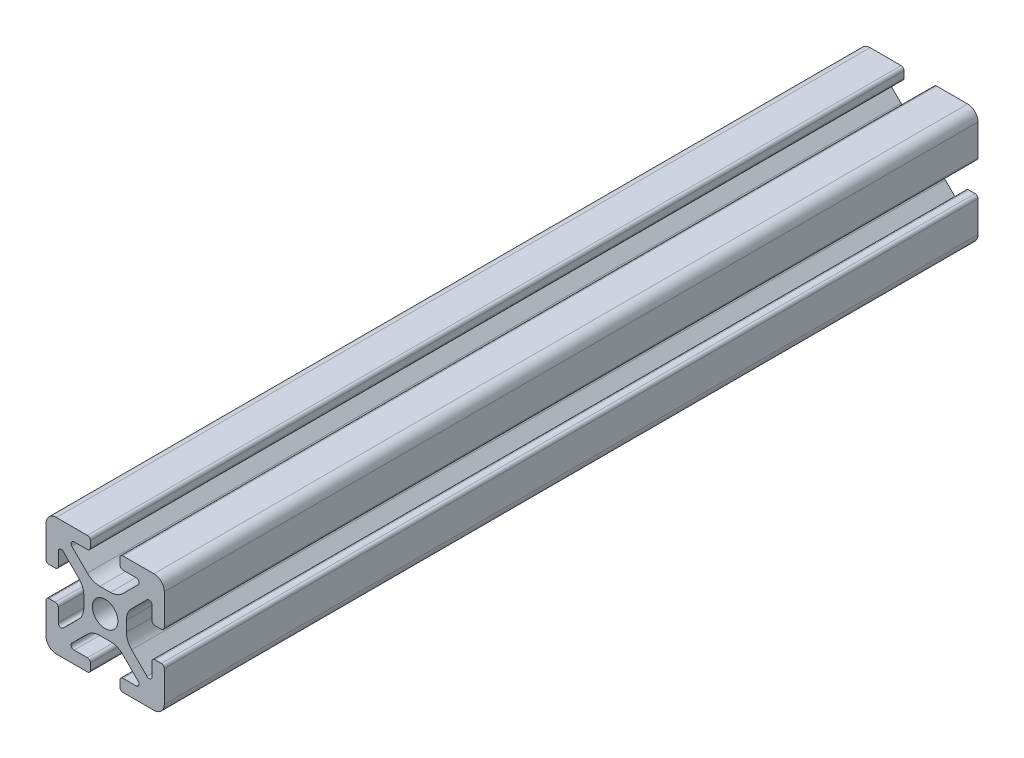
SolidWorks part; units mm, degrees
material "1060 Alloy"
ref_plane "Front Plane" through (0, 0, 0) normal (0, 0, 1) x (1, 0, 0)
ref_plane "Top Plane" through (0, 0, 0) normal (0, 1, 0) x (1, 0, 0)
ref_plane "Right Plane" through (0, 0, 0) normal (1, 0, 0) x (0, 0, -1)
sketch "Sketch2" plane through (0, 0, 0) normal (0, 0, 1) x (1, 0, 0)
  line L0 (0, 10) -> (0, -10) construction
  line L1 (-10, 0) -> (10, 0) construction
  line L2 (2.5, -10) -> (10, -10)
  line L3 (10, -10) -> (10, -2.5)
  line L4 (2.5, -10) -> (2.5, -7.9246)
  line L5 (2.5, -7.9246) -> (6.4571, -7.9246)
  line L6 (6.4571, -7.9246) -> (2.1325, -3.6)
  line L7 (0, 0) -> (10, -10) construction
  line L8 (10, -2.5) -> (7.9246, -2.5)
  line L9 (7.9246, -2.5) -> (7.9246, -6.4571)
  line L10 (7.9246, -6.4571) -> (3.6, -2.1325)
  line L11 (5.7623, -4.2948) -> (4.2948, -5.7623) construction
  circle A0 centre (0, 0) radius 2.15
  arc A1 (5.25, -7.9246) -> (5.6036, -7.0711) centre (5.25, -7.4246) ccw construction
  point P8 (0, -3.6)
  point P16 (5.0286, -5.0286)
  dimension "Center Hole Diameter" = 4.3
  dimension "D3" = 0.5
  dimension "Rail Height" = 20
  dimension "Rail Width" = 20
  dimension "T-Slot Width" = 5
  dimension "Slot Depth" = 6.4
  dimension "Slot Inner Width" = 11.5
sketch "Sketch3" plane through (0, 0, 0) normal (1, 0, 0) x (0, 0, -1)
  line L0 (-70, -10) -> (70, -10) construction
  line L1 (-44.6, 0) -> (44.6, 0) construction
  line L2 (0, 10) -> (0, -10) construction
  line L3 (0, 10) -> (0, -10) construction
  point P6 (-44.6, 0)
  point P8 (44.6, 0)
  dimension "Length" = 140
  dimension "D1" = 25.4
sketch "Sketch4" plane through (0, 0, 0) normal (0, 0, 1) x (1, 0, 0)
  line L0 (3, -10) -> (8.25, -10)
  line L1 (2.5, -10) -> (10, -10) construction
  line L2 (2.5, -10) -> (2.5, -7.9246) construction
  line L3 (2.5, -7.9246) -> (6.4571, -7.9246) construction
  line L4 (2.5, -8.4246) -> (2.5, -9.5)
  line L5 (3, -7.9246) -> (5.25, -7.9246)
  line L6 (0, -3.6) -> (0.8898, -3.6)
  line L7 (6.4571, -7.9246) -> (2.1325, -3.6) construction
  line L8 (3.0112, -4.4787) -> (5.6036, -7.0711)
  line L9 (10, -10) -> (10, -2.5) construction
  line L10 (7.9246, -6.4571) -> (3.6, -2.1325) construction
  line L11 (7.9246, -2.5) -> (7.9246, -6.4571) construction
  line L12 (7.9246, -5.25) -> (7.9246, -3)
  line L13 (10, -2.5) -> (7.9246, -2.5) construction
  line L14 (8.4246, -2.5) -> (9.5, -2.5)
  line L15 (10, -3) -> (10, -8.25)
  line L16 (7.0711, -5.6036) -> (4.4787, -3.0112)
  line L17 (3.6, 0) -> (3.6, -0.8898)
  line L18 (-10, 0) -> (10, 0) construction
  line L19 (0, -3.6) -> (0, -2.15)
  line L20 (0, 10) -> (0, -10) construction
  line L21 (3.6, 0) -> (2.15, 0)
  arc A0 (2.5, -9.5) -> (3, -10) centre (3, -9.5) ccw
  arc A1 (5.25, -7.9246) -> (5.6036, -7.0711) centre (5.25, -7.4246) ccw construction
  arc A2 (2.5, -8.4246) -> (3, -7.9246) centre (3, -8.4246) cw
  arc A3 (5.25, -7.9246) -> (5.6036, -7.0711) centre (5.25, -7.4246) ccw
  arc A4 (0.8898, -3.6) -> (3.0112, -4.4787) centre (0.8898, -6.6) cw
  arc A5 (8.25, -10) -> (10, -8.25) centre (8.25, -8.25) ccw
  arc A6 (7.0711, -5.6036) -> (7.9246, -5.25) centre (7.4246, -5.25) ccw
  arc A7 (7.9246, -3) -> (8.4246, -2.5) centre (8.4246, -3) cw
  arc A8 (9.5, -2.5) -> (10, -3) centre (9.5, -3) cw
  arc A9 (4.4787, -3.0112) -> (3.6, -0.8898) centre (6.6, -0.8898) cw
  circle A10 centre (0, 0) radius 2.15 construction
  arc A11 (0, -2.15) -> (2.15, 0) centre (0, 0) ccw
  dimension "D1" = 1.75
  dimension "D2" = 3
extrude "Boss-Extrude1" add sketch "Sketch4" along normal mid plane 140
mirror "Mirror1" about plane through (0, 0, 0) normal (1, 0, 0) of bodies 134
mirror "Mirror2" about plane through (0, 0, 0) normal (0, 1, 0) of bodies 135
sketch "Sketch5" plane through (0, 0, 70) normal (0, 0, 1) x (1, 0, 0)
  line L1 (-13.9539, 12.3566) -> (13.8334, 12.3566)
  line L2 (-13.9539, 12.3566) -> (-13.9539, -13.6827)
  line L3 (-13.9539, -13.6827) -> (13.8334, -13.6827)
  line L4 (13.8334, 12.3566) -> (13.8334, -13.6827)
extrude "Cut-Extrude1" cut sketch "Sketch5" against normal blind 2.4
equation "\"D3@Sketch2\"=\"T-Slot Width@Sketch2\"*0.1"
equation "\"D1@Sketch4\"=\"D3@Sketch2\"*3.5"
equation "\"D2@Sketch4\"=\"D3@Sketch2\"*6"
equation "\"D1@Boss-Extrude1\"=\"Length@Sketch3\""
